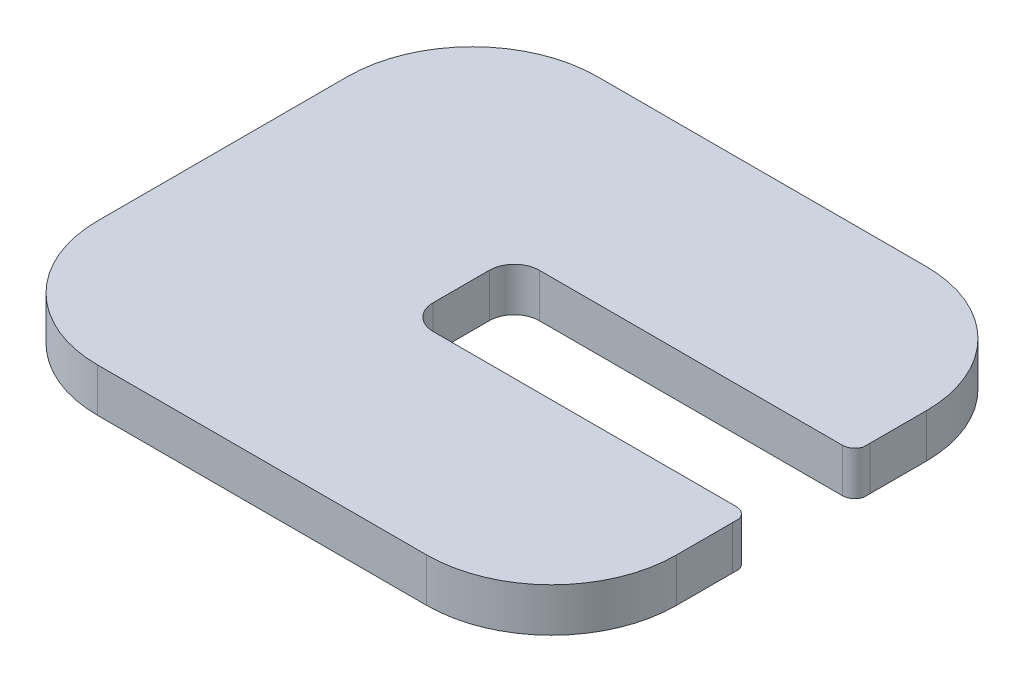
SolidWorks part; units mm, degrees
ref_plane "Front Plane" through (0, 0, 0) normal (0, 0, 1) x (1, 0, 0)
ref_plane "Top Plane" through (0, 0, 0) normal (0, 1, 0) x (1, 0, 0)
ref_plane "Right Plane" through (0, 0, 0) normal (1, 0, 0) x (0, 0, -1)
sketch "Sketch1" plane through (0, 0, 0) normal (0, 1, 0) x (1, 0, 0)
  line L0 (0, 0) -> (1120.0977, 0) construction
  line L1 (0, 0.225) -> (0, -0.225)
  line L2 (0.2, -0.425) -> (3, -0.425)
  line L3 (0.2, 0.425) -> (3, 0.425)
  line L4 (3, 0.425) -> (1.6144, 1.225)
  line L5 (1.6144, 1.225) -> (-0.3856, 1.225)
  line L6 (-0.3856, 1.225) -> (-1.1106, 0.5)
  line L7 (-1.1106, 0.5) -> (-1.4106, 0.5)
  line L8 (3, -0.425) -> (1.6144, -1.225)
  line L9 (1.6144, -1.225) -> (-0.3856, -1.225)
  line L10 (-0.3856, -1.225) -> (-1.1106, -0.5)
  line L11 (-1.1106, -0.5) -> (-1.4106, -0.5)
  arc A1 (-1.4106, 0.5) -> (-1.4106, -0.5) centre (-1.4106, 0) ccw
  arc A2 (0, -0.225) -> (0.2, -0.425) centre (0.2, -0.225) ccw
  arc A3 (0, 0.225) -> (0.2, 0.425) centre (0.2, 0.225) cw
  point P6 (0, 0)
  point P19 (0, -0.425)
  point P22 (0, 0.425)
  dimension "D9" = 0.2
  dimension "D1" = 0.85
  dimension "D2" = 3
  dimension "D3" = 30
  dimension "D4" = 0.8
  dimension "D5" = 45
  dimension "D6" = 2
  dimension "D7" = 0.3
  dimension "D8" = 0.5
extrude "Boss-Extrude1" add sketch "Sketch1" along normal blind 0.35
fillet "Fillet1" radius 0.1 2 edges at (3, 0.175, -0.425) (3, 0.175, 0.425)
sketch "Sketch2" plane through (0, 0.35, 0) normal (0, 1, 0) x (1, 0, 0)
  line L0 (2.661, 0.431) -> (2.4329, 0.348)
  line L1 (2.4158, 0.345) -> (2.3746, 0.345)
  line L2 (2.3746, 0.345) -> (2.2361, 0.425)
  line L3 (0.2, 0.425) -> (2.6268, 0.425) construction
  line L4 (2.2361, 0.425) -> (2.2361, 0.475)
  line L5 (2.2361, 0.475) -> (2.661, 0.431)
  line L6 (0, 0) -> (50000, 0) construction
  line L7 (2.2361, -0.475) -> (2.661, -0.431)
  line L8 (2.2361, -0.425) -> (2.2361, -0.475)
  line L9 (2.3746, -0.345) -> (2.2361, -0.425)
  line L10 (2.4158, -0.345) -> (2.3746, -0.345)
  line L11 (2.661, -0.431) -> (2.4329, -0.348)
  arc A0 (2.6268, 0.425) -> (2.6768, 0.6116) centre (2.6268, 0.525) ccw construction
  arc A1 (2.4329, 0.348) -> (2.4158, 0.345) centre (2.4158, 0.395) cw
  arc A2 (2.4329, -0.348) -> (2.4158, -0.345) centre (2.4158, -0.395) ccw
  point P17 (2.4246, 0.345)
  point P24 (2.4246, -0.345)
  dimension "D5" = 0.05
  dimension "D1" = 0.08
  dimension "D2" = 160
  dimension "D3" = 30
  dimension "D4" = 0.05
  dimension "D6" = 0.05
extrude "Boss-Extrude2" [suppressed] add sketch "Sketch2" against normal up to surface (0.35 mm away)
sketch "Sketch3" plane through (0, 0.35, 0) normal (0, 1, 0) x (1, 0, 0)
  line L0 (2.7234, 0.4991) -> (2.7234, 1)
  line L1 (1.7234, 2) -> (-0.9106, 2)
  line L2 (-1.9106, 1) -> (-1.9106, -1)
  line L3 (-1.7856, 0) -> (49998.2144, 0) construction
  line L4 (1.7234, -2) -> (-0.9106, -2)
  line L5 (2.7234, -0.4991) -> (2.7234, -1)
  line L6 (2.7234, -0.4991) -> (-0.2766, -0.4991)
  line L7 (-0.2766, -0.4991) -> (-0.2766, 0.4991)
  line L8 (-0.2766, 0.4991) -> (2.7234, 0.4991)
  arc A0 (2.6268, 0.425) -> (2.6768, 0.6116) centre (2.6268, 0.525) ccw construction
  arc A1 (-1.4106, 0.5) -> (-1.4106, -0.5) centre (-1.4106, 0) ccw construction
  arc A2 (1.7234, -2) -> (2.7234, -1) centre (1.7234, -1) ccw
  arc A3 (-0.9106, -2) -> (-1.9106, -1) centre (-0.9106, -1) cw
  arc A4 (-0.9106, 2) -> (-1.9106, 1) centre (-0.9106, 1) ccw
  arc A5 (2.7234, 1) -> (1.7234, 2) centre (1.7234, 1) ccw
  point P14 (-1.9106, 0)
  point P20 (2.7234, -2)
  point P23 (-1.9106, -2)
  point P26 (-1.9106, 2)
  point P29 (2.7234, 2)
  dimension "D3" = 1
  dimension "D1" = 2
  dimension "D2" = 3
extrude "Boss-Extrude3" add sketch "Sketch3" against normal up to surface (0.35 mm away) up to face at (0.4989, 0, 0)
